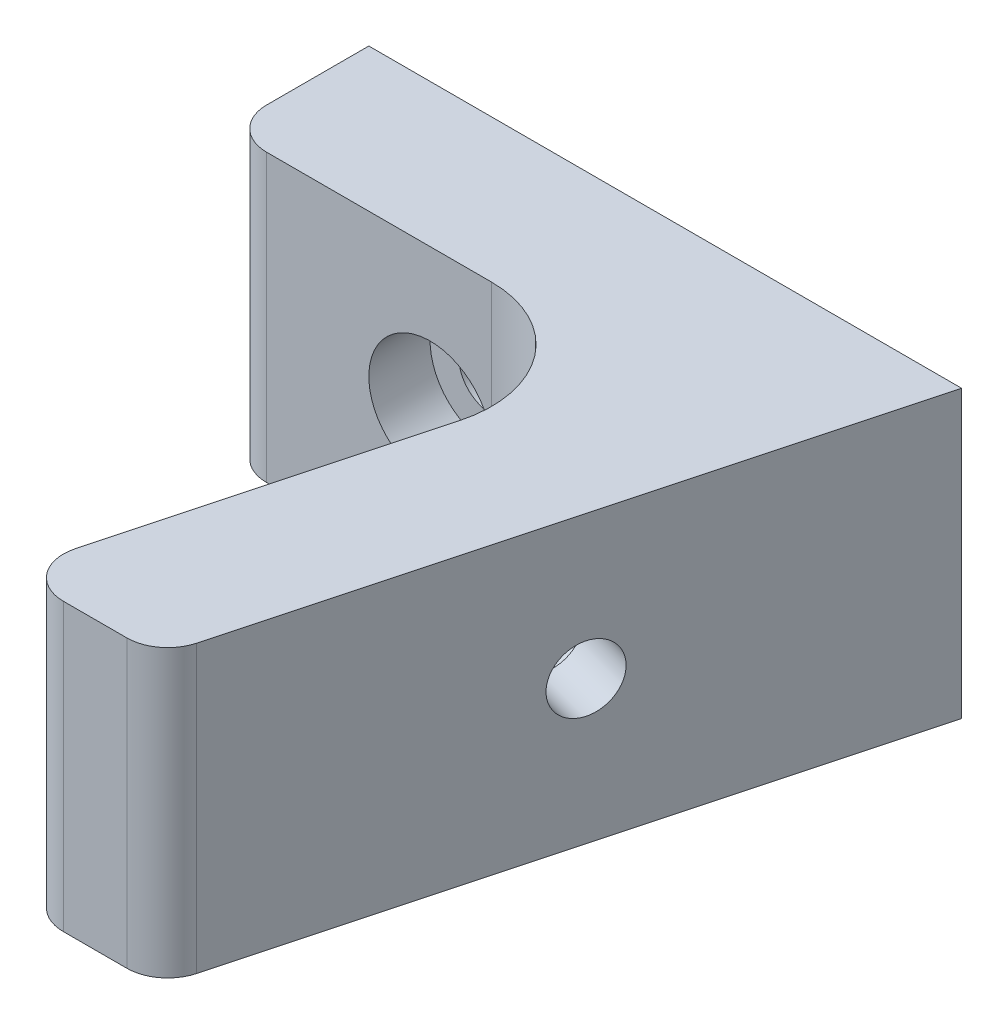
SolidWorks part; units mm, degrees
material "ABS"
ref_plane "Front" through (0, 0, 0) normal (0, 0, 1) x (1, 0, 0)
ref_plane "Top" through (0, 0, 0) normal (0, 1, 0) x (1, 0, 0)
ref_plane "Right" through (0, 0, 0) normal (1, 0, 0) x (0, 0, -1)
sketch "Esquisse1" plane through (0, 0, 0) normal (0, 1, 0) x (1, 0, 0)
  line L0 (-10, 0) -> (-10, -7)
  line L1 (-10, 0) -> (19, 0)
  line L3 (3.4466, -31) -> (10.6936, -31)
  line L4 (19, 0) -> (10.6936, -31)
  line L5 (-10, -7) -> (3, -7)
  line L6 (8.0974, -13.6431) -> (3.4466, -31)
  arc A0 (3, -7) -> (8.0974, -13.6431) centre (3, -12.2772) cw
  dimension "D5" = 3
  dimension "D1" = 10
  dimension "D2" = 19
  dimension "D3" = 75
  dimension "D4" = 31
  dimension "D6" = 7
  dimension "D7" = 7
extrude "Boss.-Extru.1" add sketch "Esquisse1" along normal mid plane 14
hole_wizard "Chambrage pour vis à tête cylindrique à 6 pans creux (ou vis CHC) M31" positions "Esquisse3" profile "Esquisse4" counterbore size "M3" standard "Ansi Metric" end condition through all
sketch "Esquisse3" plane through (0, 0, 7) normal (0, 0, 1) x (1, 0, 0)
  point P0 (0, 0)
sketch "Esquisse4" plane through (0, 0, 7) normal (1, 0, 0) x (0, -1, 0)
  line L0 (0, 0) -> (0, 7)
  line L1 (0, 7) -> (1.6, 7)
  line L3 (1.6, 7) -> (1.6, 3)
  line L4 (1.6, 3) -> (3, 3)
  line L5 (3, 3) -> (3, 0)
  line L7 (3, 0) -> (0, 0)
  line L11 (0, -6.35) -> (0, 107.95) construction
  dimension "Diamètre du perçage jusqu'au prochain" = 3.2
  dimension "Profondeur du perçage jusqu'au prochain" = 7
  dimension "Diamètre du chambrage" = 6
  dimension "Profondeur du chambrage" = 3
fillet "Congé1" radius 2 3 edges at (10.6936, 0, 31) (-10, 0, 7) (3.4466, 0, 31)
sketch "Esquisse5" plane through (17.7272, 0, 4.75) normal (0.9659, 0, 0.2588) x (0.2588, 0, -0.9659)
  line L0 (4.9176, 7) -> (4.9176, -7) construction
  circle A0 centre (-10.0824, 0) radius 1.6
  point P2 (-3.8281, 0)
  point P5 (0, 0)
  dimension "D1" = 3.2
  dimension "D2" = 15
extrude "Enlèv. mat.-Extru.1" cut sketch "Esquisse5" against normal blind 10
sketch "Esquisse6" plane through (17.7272, 0, 4.75) normal (0.9659, 0, 0.2588) x (0.2588, 0, -0.9659)
  line L1 (-7.3324, 1.5877) -> (-10.0824, 3.1754)
  line L2 (-10.0824, 3.1754) -> (-12.8324, 1.5877)
  line L3 (-12.8324, 1.5877) -> (-12.8324, -1.5877)
  line L4 (-12.8324, -1.5877) -> (-10.0824, -3.1754)
  line L5 (-10.0824, -3.1754) -> (-7.3324, -1.5877)
  line L6 (-7.3324, -1.5877) -> (-7.3324, 1.5877)
  circle A0 centre (-10.0824, 0) radius 2.75 construction
  dimension "D1" = 5.5
extrude "Enlèv. mat.-Extru.2" cut sketch "Esquisse6" against normal blind 7 from offset 3
